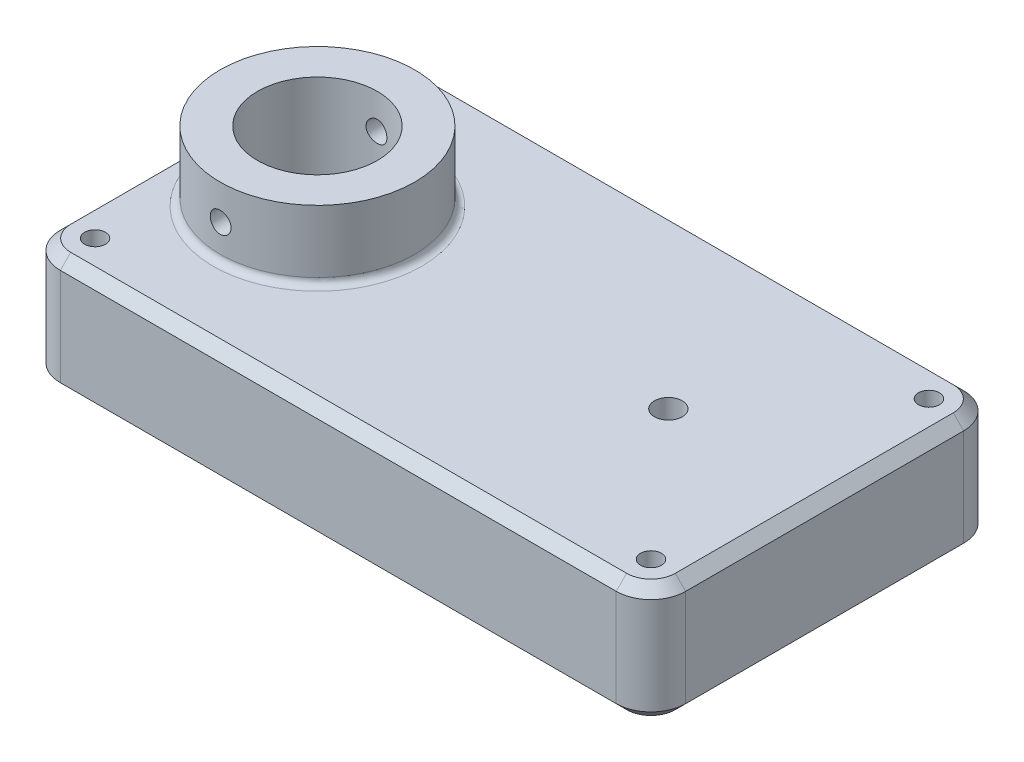
SolidWorks part; units mm, degrees
ref_plane "Front Plane" through (0, 0, 0) normal (0, 0, 1) x (1, 0, 0)
ref_plane "Top Plane" through (0, 0, 0) normal (0, 1, 0) x (1, 0, 0)
ref_plane "Right Plane" through (0, 0, 0) normal (1, 0, 0) x (0, 0, -1)
sketch "Sketch1" plane through (0, 0, 0) normal (0, 0, 1) x (1, 0, 0)
  line L1 (90, 17) -> (-90, 17)
  line L2 (90, 17) -> (90, -17)
  line L3 (90, -17) -> (-90, -17)
  line L4 (-90, 17) -> (-90, -17)
  line L5 (90, 17) -> (-90, -17) construction
  line L6 (90, -17) -> (-90, 17) construction
  point P0 (0, 0)
  dimension "D1" = 180
  dimension "D2" = 34
extrude "Boss-Extrude1" add sketch "Sketch1" along normal mid plane 100
fillet "Fillet1" radius 10 4 edges at (-90, 0, 50) (-90, 0, -50) (90, 0, -50) (90, 0, 50)
chamfer "Chamfer1" distance 3 angle 45 16 edges at (87.0711, -17, 47.0711) (90, -17, 0) (87.0711, -17, -47.0711) (0, -17, -50) (-87.0711, -17, -47.0711) (-90, -17, 0) (-87.0711, -17, 47.0711) (0, -17, 50) (-87.0711, 17, -47.0711) (0, 17, -50) (87.0711, 17, -47.0711) (90, 17, 0) (87.0711, 17, 47.0711) (0, 17, 50) (-87.0711, 17, 47.0711) (-90, 17, 0)
sketch "Sketch2" plane through (0, 17, 0) normal (0, 1, 0) x (1, 0, 0)
  circle A0 centre (-56, 0) radius 28
  dimension "D2" = 56
  dimension "D1" = 56
extrude "Boss-Extrude2" add sketch "Sketch2" along normal blind 20
sketch "Sketch3" plane through (0, 37, 0) normal (0, 1, 0) x (1, 0, 0)
  circle A0 centre (-56, 0) radius 17.25
  circle A1 centre (-56, 0) radius 28 construction
  dimension "D1" = 34.5
extrude "Cut-Extrude1" cut sketch "Sketch3" against normal through all
sketch "Sketch4" plane through (0, 17, 0) normal (0, 1, 0) x (1, 0, 0)
  circle A0 centre (45, 0) radius 4
  dimension "D2" = 8
  dimension "D1" = 45
extrude "Cut-Extrude2" cut sketch "Sketch4" against normal through all
fillet "Fillet2" radius 2 1 edges at (-28, 17, 0)
hole_wizard "Ø6.0 (6) Diameter Hole1" positions "Sketch6" profile "Sketch7" hole size "Ø6.0" standard "ANSI Metric" end condition through all
sketch "Sketch6" plane through (0, 17, 0) normal (0, 1, 0) x (1, 0, 0)
  arc A0 (-87, -40) -> (-80, -47) centre (-80, -40) ccw construction
  arc A1 (80, -47) -> (87, -40) centre (80, -40) ccw construction
  arc A2 (87, 40) -> (80, 47) centre (80, 40) ccw construction
  arc A3 (-80, 47) -> (-87, 40) centre (-80, 40) ccw construction
  point P0 (80, -40)
  point P3 (-80, -40)
  point P6 (80, 40)
  point P9 (-80, 40)
  point P12 (0, 0)
  point P16 (0, 0)
  point P17 (0, 0)
  point P21 (0, 0)
  point P25 (0, 0)
sketch "Sketch7" plane through (80, 17, 40) normal (1, 0, 0) x (0, 0, 1)
  line L0 (0, 0) -> (0, 34)
  line L1 (0, 34) -> (3, 34)
  line L2 (3, 34) -> (3, 0)
  line L5 (3, 0) -> (0, 0)
  line L11 (0, -6.35) -> (0, 107.95) construction
  dimension "Thru Hole Dia." = 6
  dimension "Thru Hole Depth" = 34
sketch "Sketch8" plane through (0, 0, 0) normal (0, 0, 1) x (1, 0, 0)
  line L0 (-56, 37) -> (-56, 27) construction
  line L1 (-28, 37) -> (-84, 37) construction
  line L2 (80, -17) -> (-80, -17) construction
  circle A0 centre (-56, 27) radius 3
  dimension "D2" = 6
  dimension "D1" = 44
extrude "Cut-Extrude3" cut sketch "Sketch8" against normal through all both and the other way through all
